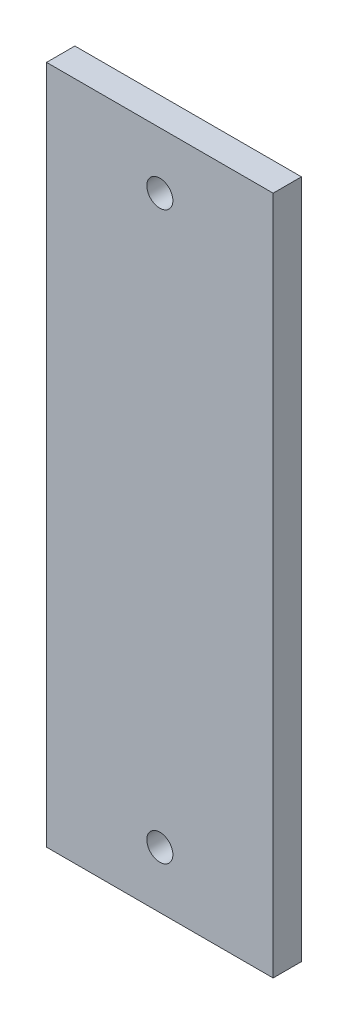
SolidWorks part; units mm, degrees
ref_plane "Front Plane" through (0, 0, 0) normal (0, 0, 1) x (1, 0, 0)
ref_plane "Top Plane" through (0, 0, 0) normal (0, 1, 0) x (1, 0, 0)
ref_plane "Right Plane" through (0, 0, 0) normal (1, 0, 0) x (0, 0, -1)
sketch "Sketch2" plane through (0, 0, 0) normal (0, 0, 1) x (1, 0, 0)
  line L0 (12.7, 76.2) -> (12.7, 0) construction
  line L1 (0, 0) -> (25.4, 0)
  line L2 (0, 0) -> (0, 76.2)
  line L3 (0, 76.2) -> (25.4, 76.2)
  line L4 (25.4, 0) -> (25.4, 76.2)
  circle A0 centre (12.7, 69.85) radius 1.4605
  circle A1 centre (12.7, 6.35) radius 1.4605
  dimension "D3" = 2.921
  dimension "D5" = 2.921
  dimension "D1" = 25.4
  dimension "D2" = 76.2
  dimension "D4" = 6.35
  dimension "D6" = 6.35
extrude "Boss-Extrude1" add sketch "Sketch2" along normal blind 3.175
